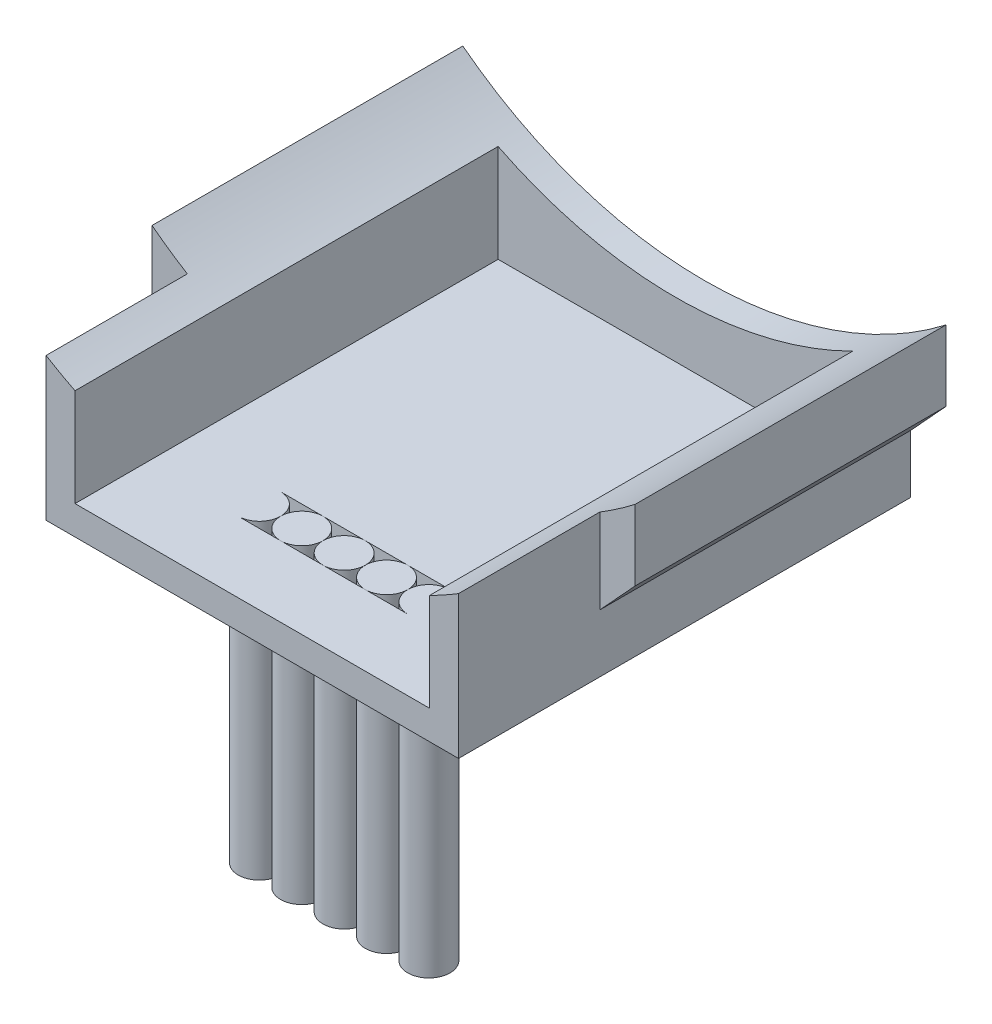
SolidWorks part; units mm, degrees
ref_plane "Plan de face" through (0, 0, 0) normal (0, 0, 1) x (1, 0, 0)
ref_plane "Plan de dessus" through (0, 0, 0) normal (0, 1, 0) x (1, 0, 0)
ref_plane "Plan de droite" through (0, 0, 0) normal (1, 0, 0) x (0, 0, -1)
sketch "Esquisse1" plane through (0, 0, 0) normal (0, 0, 1) x (1, 0, 0)
  line L0 (-23.65, 0) -> (27.8675, 0) construction
  line L1 (0, 9.9898) -> (0, -18.7945) construction
  line L2 (-7.3, -17) -> (7.3, -17)
  line L3 (-7.3, -17) -> (-7.3, -11.9461)
  line L4 (7.3, -17) -> (7.3, -11.9461)
  line L5 (-6.275, -15.975) -> (6.275, -15.975)
  line L6 (6.275, -15.975) -> (6.275, -12.515)
  line L7 (-6.275, -15.975) -> (-6.275, -12.515)
  arc A0 (-7.3, -11.9461) -> (-6.275, -12.515) centre (0, 0) ccw
  arc A1 (6.275, -12.515) -> (7.3, -11.9461) centre (0, 0) ccw
  point P10 (0, -17)
  point P15 (0, -15.975)
  dimension "D1" = 28
  dimension "D2" = 14.6
  dimension "D3" = 17
  dimension "D5" = 15.975
  dimension "D6" = 6.275
extrude "Boss.-Extru.1" add sketch "Esquisse1" against normal blind 16
sketch "Esquisse2" plane through (0, -17, 0) normal (0, -1, 0) x (1, 0, 0)
  line L1 (-7.3, -16) -> (7.3, -16)
  line L2 (-7.3, -16) -> (-7.3, -14.975)
  line L3 (-7.3, -14.975) -> (7.3, -14.975)
  line L4 (7.3, -16) -> (7.3, -14.975)
  dimension "D1" = 1.025
extrude "Boss.-Extru.2" add sketch "Esquisse2" against normal up to surface (5.0539 mm away)
sketch "Esquisse3" plane through (0, 0, -16) normal (0, 0, -1) x (-1, 0, 0)
  line L0 (-7.3, -11.9461) -> (-7.3, -14.9461)
  line L1 (-7.3, -17) -> (-7.3, -11.9461) construction
  line L2 (-7.3, -14.9461) -> (-8.55, -13.5859)
  line L3 (-8.55, -13.5859) -> (-8.55, -11.0859)
  line L4 (0, -14) -> (0, 0) construction
  line L5 (8.55, -13.5859) -> (8.55, -11.0859)
  line L6 (7.3, -14.9461) -> (8.55, -13.5859)
  line L7 (7.3, -11.9461) -> (7.3, -14.9461)
  arc A0 (7.3, -11.9461) -> (8.55, -11.0859) centre (0, 0) ccw
  arc A1 (-8.55, -11.0859) -> (-7.3, -11.9461) centre (0, 0) ccw
  dimension "D1" = 3
  dimension "D2" = 2.5
  dimension "D4" = 1.25
extrude "Boss.-Extru.3" add sketch "Esquisse3" against normal blind 11
sketch "Esquisse4" plane through (0, -17, 0) normal (0, -1, 0) x (1, 0, 0)
  line L0 (0, 0) -> (0, -16) construction
  line L1 (-7.3, 0) -> (7.3, 0) construction
  line L2 (-7.3, -16) -> (7.3, -16) construction
  line L4 (-3, -2.5) -> (3, -2.5)
  line L5 (-3, -2.5) -> (-3, -4) construction
  line L6 (-3, -4) -> (3, -4)
  line L7 (3, -2.5) -> (3, -4) construction
  arc A0 (-3, -2.5) -> (-3, -4) centre (-3, -3.25) ccw
  arc A1 (3, -2.5) -> (3, -4) centre (3, -3.25) cw
  point P10 (0, -2.5)
  dimension "D1" = 6
  dimension "D2" = 1.5
  dimension "D3" = 2.5
extrude "Enlèv. mat.-Extru.1" cut sketch "Esquisse4" against normal blind 11
sketch "Esquisse5" plane through (0, -15.975, 0) normal (0, 1, 0) x (1, 0, 0)
  line L0 (3, 3.25) -> (-3, 3.25) construction
  circle A0 centre (3, 3.25) radius 0.75
  circle A1 centre (-3, 3.25) radius 0.75
  circle A2 centre (0, 3.25) radius 0.75
  circle A3 centre (1.5, 3.25) radius 0.75
  circle A4 centre (-1.5, 3.25) radius 0.75
  dimension "D1" = 1.5
  dimension "D2" = 1.5
  dimension "D3" = 1.5
extrude "Boss.-Extru.4" add sketch "Esquisse5" against normal blind 11
